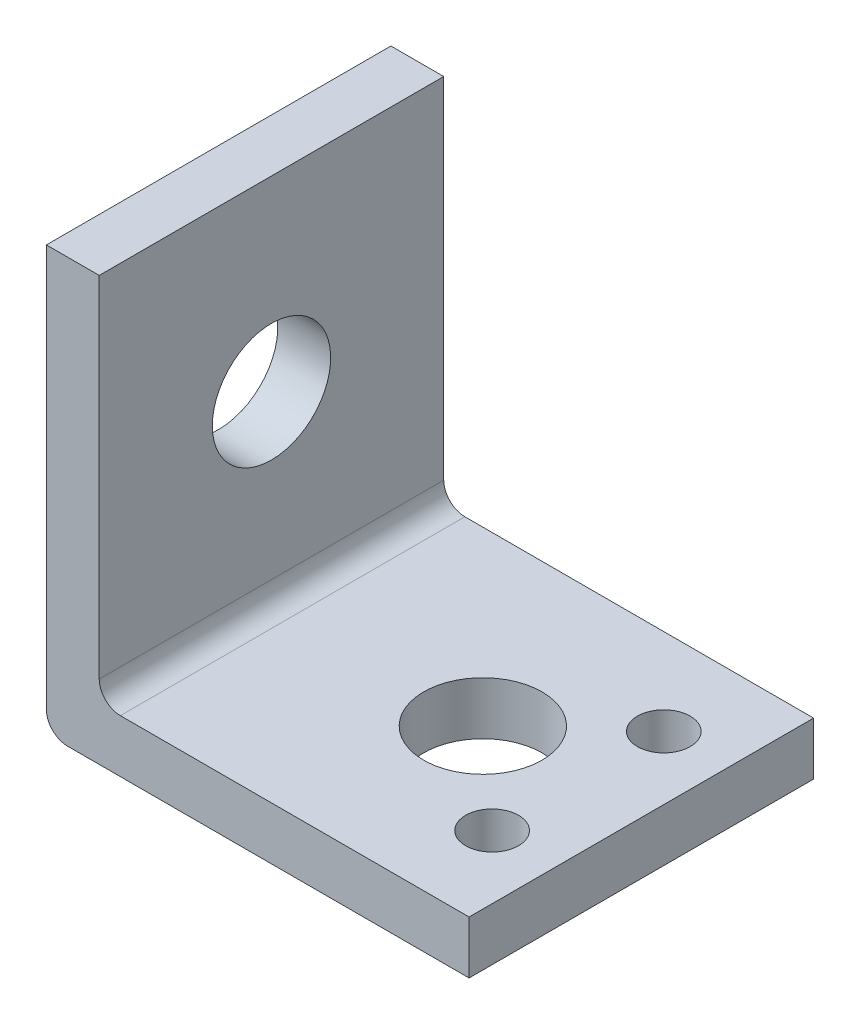
SolidWorks part; units mm, degrees
ref_plane "前视基准面" through (0, 0, 0) normal (0, 0, 1) x (1, 0, 0)
ref_plane "上视基准面" through (0, 0, 0) normal (0, 1, 0) x (1, 0, 0)
ref_plane "右视基准面" through (0, 0, 0) normal (1, 0, 0) x (0, 0, -1)
sketch "草图1" plane through (0, 0, 0) normal (0, 0, 1) x (1, 0, 0)
  line L0 (2.54, 0) -> (50.8, 0)
  line L1 (50.8, 0) -> (50.8, 6.35)
  line L2 (50.8, 6.35) -> (8.89, 6.35)
  line L3 (0, 2.54) -> (0, 50.901)
  line L4 (0, 50.901) -> (6.35, 50.901)
  line L5 (6.35, 50.901) -> (6.35, 8.89)
  arc A0 (6.35, 8.89) -> (8.89, 6.35) centre (8.89, 8.89) ccw
  arc A1 (0, 2.54) -> (2.54, 0) centre (2.54, 2.54) ccw
  point P11 (0, 0)
  dimension "D1" = 2.54
  dimension "D2" = 2.54
extrude "凸台-拉伸1" add sketch "草图1" along normal blind 41.402
ref_plane "基准面1" through (0, 0, 0) normal (0, -1, 0) x (-1, 0, 0)
sketch "草图3" plane through (0, 0, 0) normal (0, -1, 0) x (-1, 0, 0)
  line L0 (0, -20.701) -> (-31.75, -20.701) construction
  line L1 (0, -41.402) -> (0, 0) construction
  circle A0 centre (-31.75, -20.701) radius 7.112
ref_plane "基准面2" through (0, 0, 0) normal (-1, 0, 0) x (0, 0, 1)
sketch "草图4" plane through (0, 0, 0) normal (-1, 0, 0) x (0, 0, 1)
  line L0 (20.701, 0) -> (20.701, 28.448) construction
  line L1 (13.589, 0) -> (27.813, 0) construction
  circle A0 centre (20.701, 28.448) radius 7.112
extrude "切除-拉伸1" cut sketch "草图4" against normal through all
extrude "切除-拉伸2" cut sketch "草图3" against normal through all contours A0
sketch "Sketch1" plane through (0, 0, 0) normal (0, -1, 0) x (-1, 0, 0)
  line L0 (-50.8, 0) -> (-43.18, 0) construction
  line L1 (-2.54, 0) -> (-50.8, 0) construction
  line L2 (-43.18, -10.3822) -> (-43.18, -20.701) construction
  line L3 (-43.18, -10.3822) -> (-50.8, -10.3822) construction
  line L4 (-50.8, -41.402) -> (-50.8, 0) construction
  line L5 (-50.8, -20.701) -> (0, -20.701) construction
  line L6 (0, -22.7711) -> (0, 22.7711) construction
  circle A0 centre (-43.18, -10.3822) radius 3.175
  circle A1 centre (-43.18, -31.0197) radius 3.175
extrude "Cut-Extrude1" cut sketch "Sketch1" against normal through all
